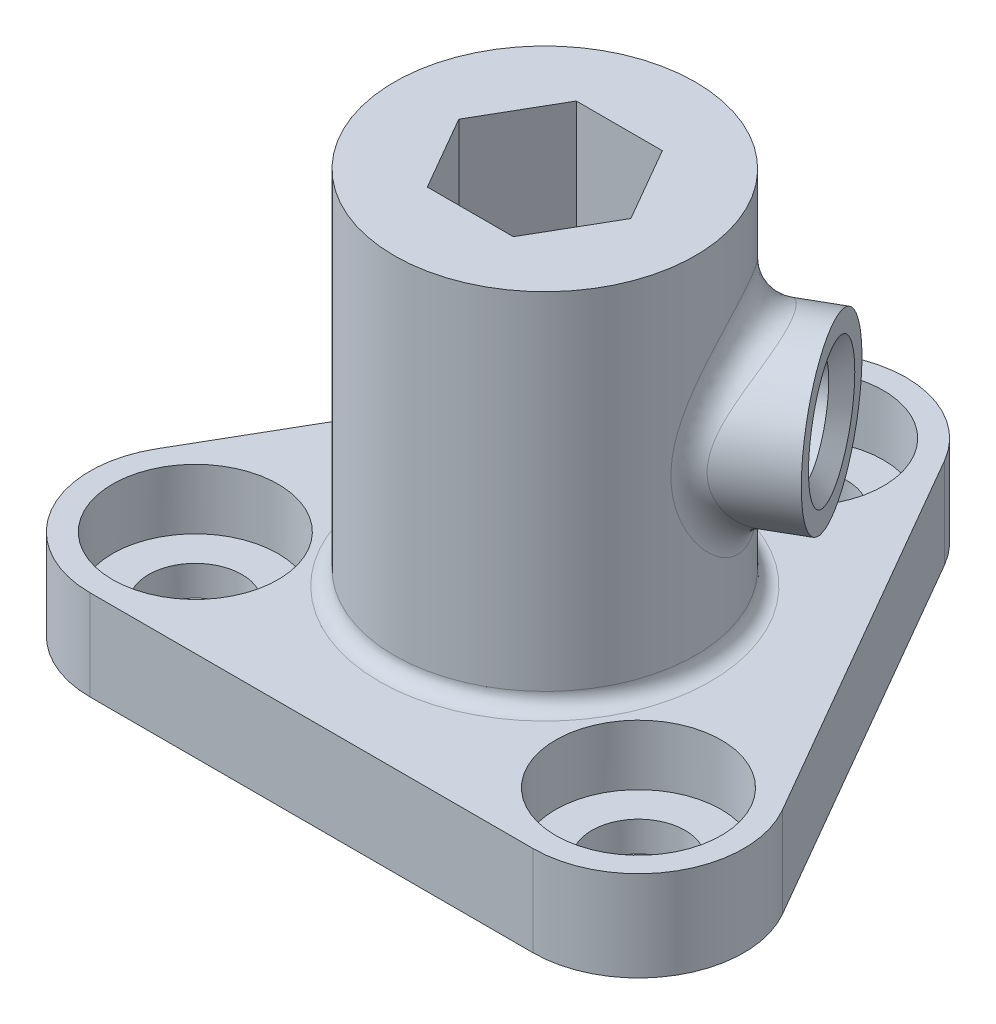
SolidWorks part; units mm, degrees
ref_plane "Front Plane" through (0, 0, 0) normal (0, 0, 1) x (1, 0, 0)
ref_plane "Top Plane" through (0, 0, 0) normal (0, 1, 0) x (1, 0, 0)
ref_plane "Right Plane" through (0, 0, 0) normal (1, 0, 0) x (0, 0, -1)
sketch "Sketch1" plane through (0, 0, 0) normal (1, 0, 0) x (0, 0, -1)
  line L1 (0, 0) -> (12, 0)
  line L2 (0, 0) -> (0, 5.3535)
  line L3 (5, 3) -> (12, 3)
  line L4 (12, 0) -> (12, 3)
  line L6 (0, 5.3535) -> (0, 15)
  line L7 (0, 15) -> (5, 15)
  line L8 (5, 3) -> (5, 15)
  dimension "D1" = 15
  dimension "6" = 5
  dimension "D3" = 3
  dimension "D4" = 7
revolve "Revolve1" add sketch "Sketch1" angle 360 about L6
sketch "Sketch4" plane through (0, 3, 0) normal (0, 1, 0) x (1, 0, 0)
  circle A0 centre (0, 8.5) radius 2.75
  circle A1 centre (7.3612, -4.25) radius 2.75
  circle A2 centre (-7.3612, -4.25) radius 2.75
  circle A6 centre (0, 0) radius 8.5 construction
  point P15 (0, 0)
  dimension "D2" = 17
  dimension "D3" = 5.5
  dimension "D1" = 3
extrude "Cut-Extrude4" cut sketch "Sketch4" against normal offset from surface (2 mm away) 1 up to face at (0, 0, -12)
sketch "Sketch5" plane through (0, 3, 0) normal (0, 1, 0) x (1, 0, 0)
  line L0 (-3.0311, 10.25) -> (-10.3923, -2.5)
  line L1 (-7.3612, -7.75) -> (7.3612, -7.75)
  line L2 (3.0311, 10.25) -> (10.3923, -2.5)
  arc A0 (3.0311, 10.25) -> (-3.0311, 10.25) centre (0, 8.5) ccw
  arc A1 (7.3612, -7.75) -> (10.3923, -2.5) centre (7.3612, -4.25) ccw
  arc A2 (-10.3923, -2.5) -> (-7.3612, -7.75) centre (-7.3612, -4.25) ccw
  circle A3 centre (0, 0) radius 12 construction
extrude "Cut-Extrude5" cut sketch "Sketch5" against normal through all flip side to cut
sketch "Sketch2" plane through (0, 15, 0) normal (0, 1, 0) x (1, 0, 0)
  line L0 (10.3923, -2.5) -> (3.0311, 10.25) construction
  line L1 (2.8579, 0) -> (1.4289, 2.475)
  line L2 (1.4289, 2.475) -> (-1.4289, 2.475)
  line L3 (-1.4289, 2.475) -> (-2.8579, 0)
  line L4 (-2.8579, 0) -> (-1.4289, -2.475)
  line L5 (-1.4289, -2.475) -> (1.4289, -2.475)
  line L6 (1.4289, -2.475) -> (2.8579, 0)
  circle A0 centre (0, 0) radius 2.475 construction
  dimension "D1" = 4.95
extrude "Cut-Extrude2" cut sketch "Sketch2" against normal offset from surface (8 mm away) 4 up to face at (0, 3, -5.75)
ref_plane "Plane1" through (6.0405, 0, -3.4875) normal (-0.866, 0, 0.5) x (0.5, 0, 0.866)
sketch "Sketch3" plane through (6.0405, 0, -3.4875) normal (0.866, 0, -0.5) x (-0.5, 0, -0.866)
  line L0 (0, 15) -> (0, 3) construction
  line L1 (1.4289, 15) -> (-1.4289, 15) construction
  line L3 (5, 3) -> (-5, 3) construction
  circle A0 centre (0, 9) radius 2.75
  point P10 (0, 9)
  dimension "D1" = 5.5
extrude "Boss-Extrude1" add sketch "Sketch3" against normal up to next
sketch "Sketch6" plane through (6.0405, 0, -3.4875) normal (0.866, 0, -0.5) x (-0.5, 0, -0.866)
  circle A0 centre (0, 9) radius 1.6
  dimension "D1" = 3.2
extrude "Cut-Extrude6" cut sketch "Sketch6" against normal up to next
fillet "Fillet1" radius 0.5 1 edges at (0, 3, -5)
chamfer "Chamfer1" distance 0.5 angle 45 1 edges at (5.2405, 9, -4.8731)
fillet "Fillet2" radius 1 1 edges at (4.9921, 8.766, 0.2817)
sketch "Sketch7" plane through (0, 3, 0) normal (0, 1, 0) x (1, 0, 0)
  circle A0 centre (0, 8.5) radius 1.55
  circle A1 centre (7.3612, -4.25) radius 1.55
  circle A2 centre (-7.3612, -4.25) radius 1.55
  dimension "D1" = 3.1
extrude "Cut-Extrude7" cut sketch "Sketch7" against normal through all
